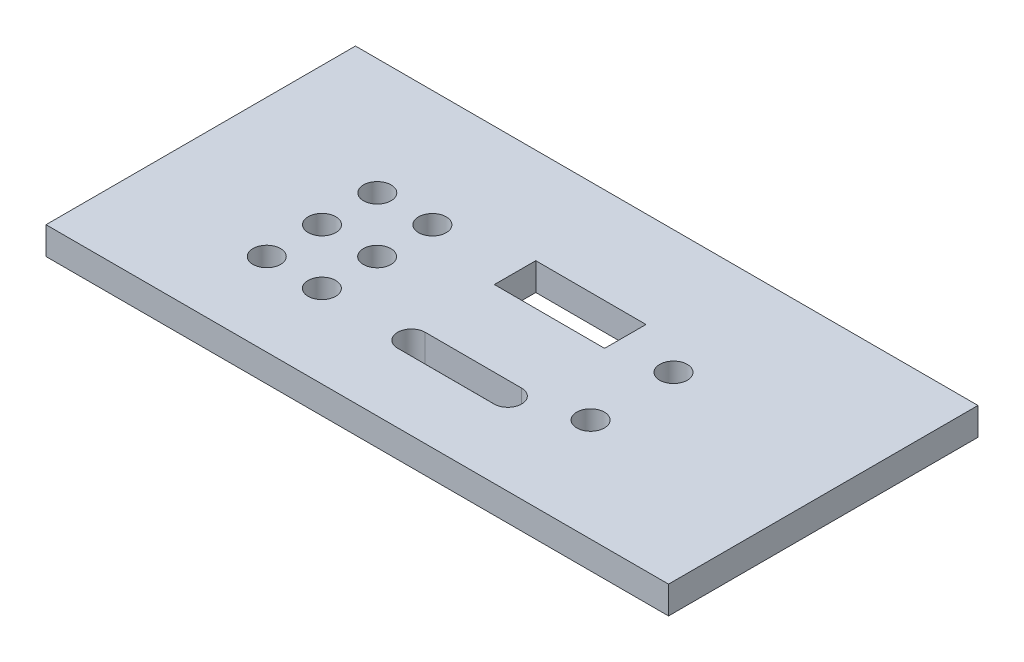
SolidWorks part; units mm, degrees
ref_plane "Front Plane" through (0, 0, 0) normal (0, 0, 1) x (1, 0, 0)
ref_plane "Top Plane" through (0, 0, 0) normal (0, 1, 0) x (1, 0, 0)
ref_plane "Right Plane" through (0, 0, 0) normal (1, 0, 0) x (0, 0, -1)
sketch "Sketch2" plane through (0, 0, 0) normal (0, 1, 0) x (1, 0, 0)
  line L1 (112.8005, -56.0742) -> (-112.8005, -56.0742)
  line L2 (112.8005, -56.0742) -> (112.8005, 56.0742)
  line L3 (112.8005, 56.0742) -> (-112.8005, 56.0742)
  line L4 (-112.8005, -56.0742) -> (-112.8005, 56.0742)
  line L5 (112.8005, -56.0742) -> (-112.8005, 56.0742) construction
  line L6 (112.8005, 56.0742) -> (-112.8005, -56.0742) construction
  point P0 (0, 0)
extrude "Boss-Extrude1" add sketch "Sketch2" along normal blind 10
sketch "Sketch3" plane through (0, 10, 0) normal (0, 1, 0) x (1, 0, 0)
  line L0 (-112.8005, -56.0742) -> (112.8005, -56.0742) construction
  line L1 (-112.8005, 56.0742) -> (-112.8005, -56.0742) construction
  point P0 (-41.5332, -6.3177)
  line B0 (-12.7617, 21.3833) -> (27.2383, 21.3268)
  line B1 (-12.7617, 21.3833) -> (-12.7829, 6.3833)
  line B2 (-12.7829, 6.3833) -> (27.2171, 6.3268)
  line B3 (27.2383, 21.3268) -> (27.2171, 6.3268)
  circle B4 centre (47.1817, -18.7014) radius 5
  circle B5 centre (47.2241, 11.2985) radius 5
  circle B6 centre (-42.7723, 13.9257) radius 5
  circle B7 centre (-62.7722, 13.954) radius 5
  circle B8 centre (-62.8005, -6.046) radius 5
  circle B9 centre (-62.8288, -26.046) radius 5
  circle B10 centre (-42.8005, -6.0742) radius 5
  circle B11 centre (-42.8288, -26.0742) radius 5
  line B12 (24.6641, -31.1696) -> (-10.3359, -31.1202)
  arc B13 (-10.3218, -21.1202) -> (-10.3359, -31.1202) centre (-10.3288, -26.1202) ccw
  line B14 (24.6782, -21.1696) -> (-10.3218, -21.1202)
  arc B15 (24.6641, -31.1696) -> (24.6782, -21.1696) centre (24.6711, -26.1696) ccw
  dimension "D1" = 50
  dimension "D2" = 70
sketch_block_instance "CustomBlock1-1"
sketch_block "CustomBlock1" parameters "D7"=10, "D8"=5, "D1"=30, "D2"=40, "D3"=40, "D4"=40, "D5"=15, "D6"=2.5, "D9"=35, "D10"=90, "D11"=20, "D12"=20
extrude "Cut-Extrude1" cut sketch "Sketch3" against normal through all
